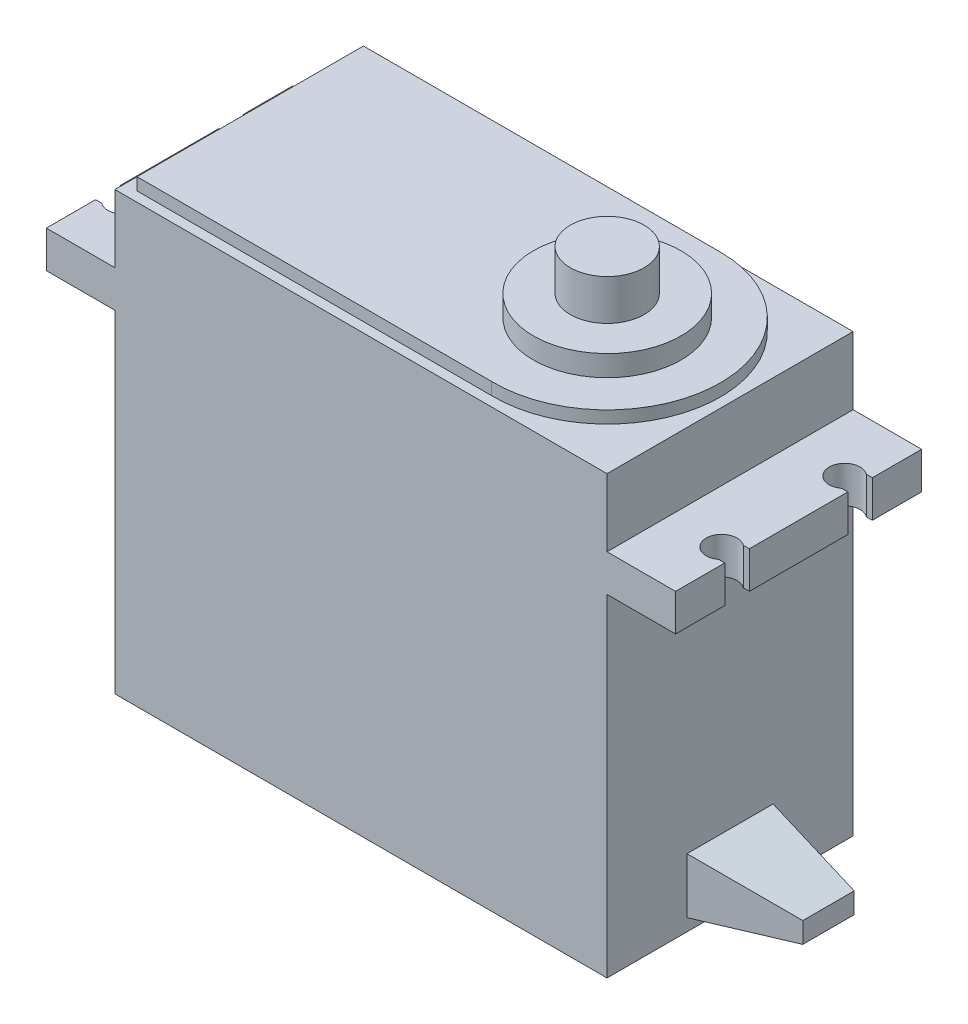
SolidWorks part; units mm, degrees
ref_plane "Plano frontal" through (0, 0, 0) normal (0, 0, 1) x (1, 0, 0)
ref_plane "Plano superior" through (0, 0, 0) normal (0, 1, 0) x (1, 0, 0)
ref_plane "Plano direito" through (0, 0, 0) normal (1, 0, 0) x (0, 0, -1)
sketch "Esboço1" plane through (0, 0, 0) normal (0, 0, 1) x (1, 0, 0)
  line L0 (20, -0.7679) -> (25.5689, -0.7679)
  line L1 (25.5689, -0.7679) -> (25.5689, -3.7679)
  line L2 (25.5689, -3.7679) -> (20, -3.7679)
  line L3 (20, -3.7679) -> (20, -30.7679)
  line L4 (20, -30.7679) -> (-20, -30.7679)
  line L5 (0, -30.7679) -> (0, 0) construction
  line L6 (20, -0.7679) -> (20, 4.7321)
  line L7 (20, 4.7321) -> (-20, 4.7321)
  line L8 (-20, -0.7679) -> (-20, 4.7321)
  line L9 (-20, -3.7679) -> (-20, -30.7679)
  line L10 (-25.5689, -3.7679) -> (-20, -3.7679)
  line L11 (-25.5689, -0.7679) -> (-25.5689, -3.7679)
  line L12 (-20, -0.7679) -> (-25.5689, -0.7679)
  point P11 (0, 4.7321)
  dimension "D1" = 40
  dimension "D2" = 27
  dimension "D3" = 3
  dimension "D4" = 5.5
extrude "Ressalto-extrusão1" add sketch "Esboço1" along normal mid plane 20
sketch "Esboço6" plane through (0, -0.7679, 0) normal (0, 1, 0) x (1, 0, 0)
  line L0 (0, 10) -> (0, -10) construction
  line L1 (20, 10) -> (-20, 10) construction
  line L2 (20, -10) -> (-20, -10) construction
  line L3 (24.315, 5) -> (24.315, -5) construction
  line L4 (20, -10) -> (20, 10) construction
  line L5 (25.5689, 4) -> (25.0714, 4)
  line L6 (25.5689, -10) -> (25.5689, 10) construction
  line L7 (25.0714, 6) -> (25.5689, 6)
  line L8 (24.315, 5) -> (25.5689, 5) construction
  line L9 (25.5689, 6) -> (25.5689, 4)
  line L10 (20, 0) -> (25.5689, 0) construction
  line L11 (25.5689, -6) -> (25.5689, -4)
  line L12 (25.0714, -6) -> (25.5689, -6)
  line L13 (25.5689, -4) -> (25.0714, -4)
  line L14 (-25.5689, -4) -> (-25.0714, -4)
  line L15 (-25.0714, -6) -> (-25.5689, -6)
  line L16 (-25.5689, -6) -> (-25.5689, -4)
  line L17 (-25.5689, 6) -> (-25.5689, 4)
  line L18 (-25.0714, 6) -> (-25.5689, 6)
  line L19 (-25.5689, 4) -> (-25.0714, 4)
  arc A0 (25.0714, 6) -> (25.0714, 4) centre (24.315, 5) ccw
  arc A1 (25.0714, -4) -> (25.0714, -6) centre (24.315, -5) ccw
  arc A2 (-25.0714, -4) -> (-25.0714, -6) centre (-24.315, -5) cw
  arc A3 (-25.0714, 6) -> (-25.0714, 4) centre (-24.315, 5) cw
  point P14 (24.315, 0)
  point P17 (20, 0)
  line M4 (25.5689, -10) -> (25.5689, 10)
  dimension "D1" = 48.63
  dimension "D2" = 10
  dimension "D3" = 2
extrude "Corte-extrusão1" cut sketch "Esboço6" against normal blind 10 contours L7 A0 L5 M4 | L13 A1 L12 M4 | A3 L18 L17 L19 | A2 L14 L16 L15
sketch "Esboço3" plane through (0, 4.7321, 0) normal (0, 1, 0) x (1, 0, 0)
  line L0 (20, -10) -> (-20, -10) construction
  line L1 (-19, 9.2025) -> (10.015, 9.2025)
  line L2 (-19, 9.2025) -> (-19, -9.2)
  line L3 (-19, -9.2) -> (9.8, -9.2)
  arc A0 (25.0714, -4) -> (25.0714, -6) centre (24.315, -5) ccw construction
  arc A1 (9.8, -9.2) -> (10.015, 9.2025) centre (10.015, 0) ccw
  point P0 (0, 0)
  dimension "D1" = 0.8
  dimension "D2" = 14.3
extrude "Ressalto-extrusão2" add sketch "Esboço3" along normal blind 1
sketch "Esboço4" plane through (0, 5.7321, 0) normal (0, 1, 0) x (1, 0, 0)
  circle A0 centre (10.015, 0) radius 3
extrude "Ressalto-extrusão3" add sketch "Esboço4" along normal blind 5
sketch "Esboço5" plane through (0, 5.7321, 0) normal (0, 1, 0) x (1, 0, 0)
  circle A0 centre (10.015, 0) radius 6
  arc A1 (25.0714, -4) -> (25.0714, -6) centre (24.315, -5) ccw construction
  dimension "D1" = 14.3
extrude "Ressalto-extrusão4" add sketch "Esboço5" along normal blind 1.7
sketch "Esboço7" plane through (20, 0, 0) normal (1, 0, 0) x (0, 0, -1)
  line L0 (-10, -30.7679) -> (10, -30.7679) construction
  line L1 (-3.5, -25.2679) -> (3.5, -25.2679)
  line L2 (-3.5, -25.2679) -> (-3.5, -29.7679)
  line L3 (-3.5, -29.7679) -> (3.5, -29.7679)
  line L4 (3.5, -25.2679) -> (3.5, -29.7679)
  line L5 (-3.5, -25.2679) -> (3.5, -29.7679) construction
  line L6 (-3.5, -29.7679) -> (3.5, -25.2679) construction
  point P0 (0, -27.5179)
  point P7 (0, 0)
  point P8 (0, -30.7679)
  dimension "D1" = 5.5
  dimension "D2" = 1
  dimension "D3" = 7
extrude "Ressalto-extrusão5" add sketch "Esboço7" along normal blind 8 draft 10
